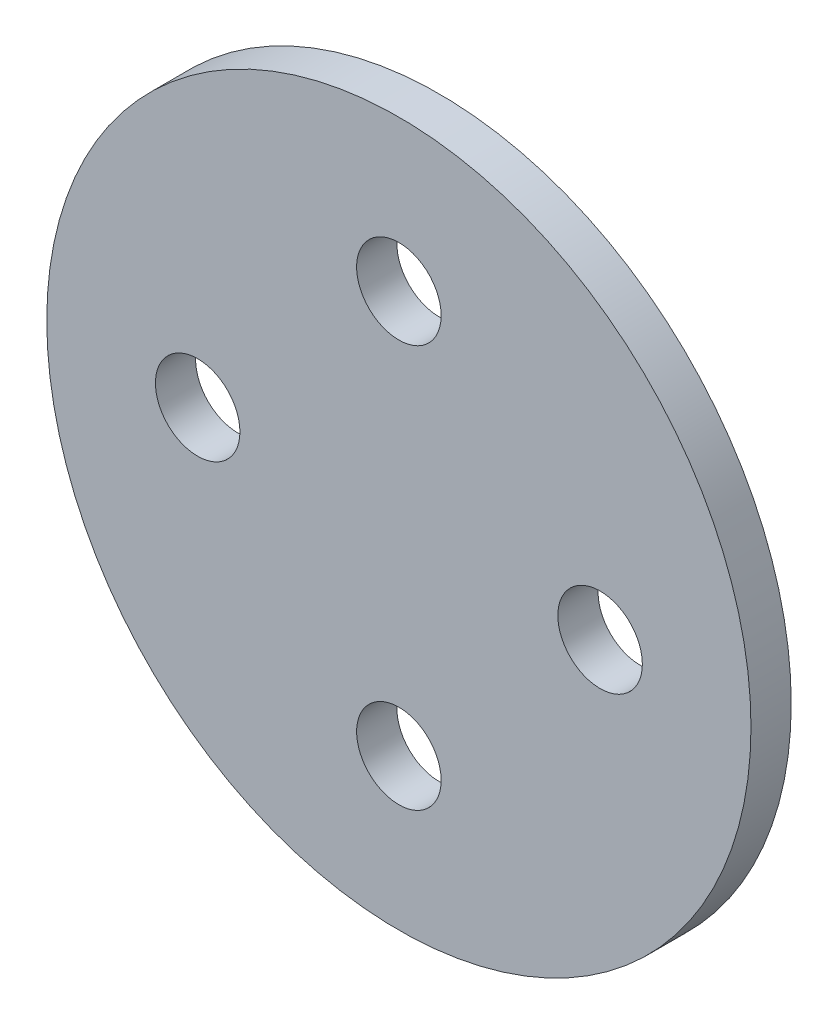
SolidWorks part; units mm, degrees
material "Thornel Mat VMA"
ref_plane "前视基准面" through (0, 0, 0) normal (0, 0, 1) x (1, 0, 0)
ref_plane "上视基准面" through (0, 0, 0) normal (0, 1, 0) x (1, 0, 0)
ref_plane "右视基准面" through (0, 0, 0) normal (1, 0, 0) x (0, 0, -1)
other "Configuration Table"
sketch "草图1" plane through (0, 0, 0) normal (0, 0, 1) x (1, 0, 0)
  circle A1 centre (0, 0) radius 17.5
  circle A2 centre (0, 0) radius 10 construction
  circle A3 centre (0, 10) radius 2.1
  circle A4 centre (10, 0) radius 2.1
  circle A5 centre (0, -10) radius 2.1
  circle A6 centre (-10, 0) radius 2.1
  point P16 (0, 0)
  dimension "D2" = 35
  dimension "D3" = 20
  dimension "D4" = 4.2
  dimension "D5" = 4
extrude "凸台-拉伸1" add sketch "草图1" along normal blind 2
